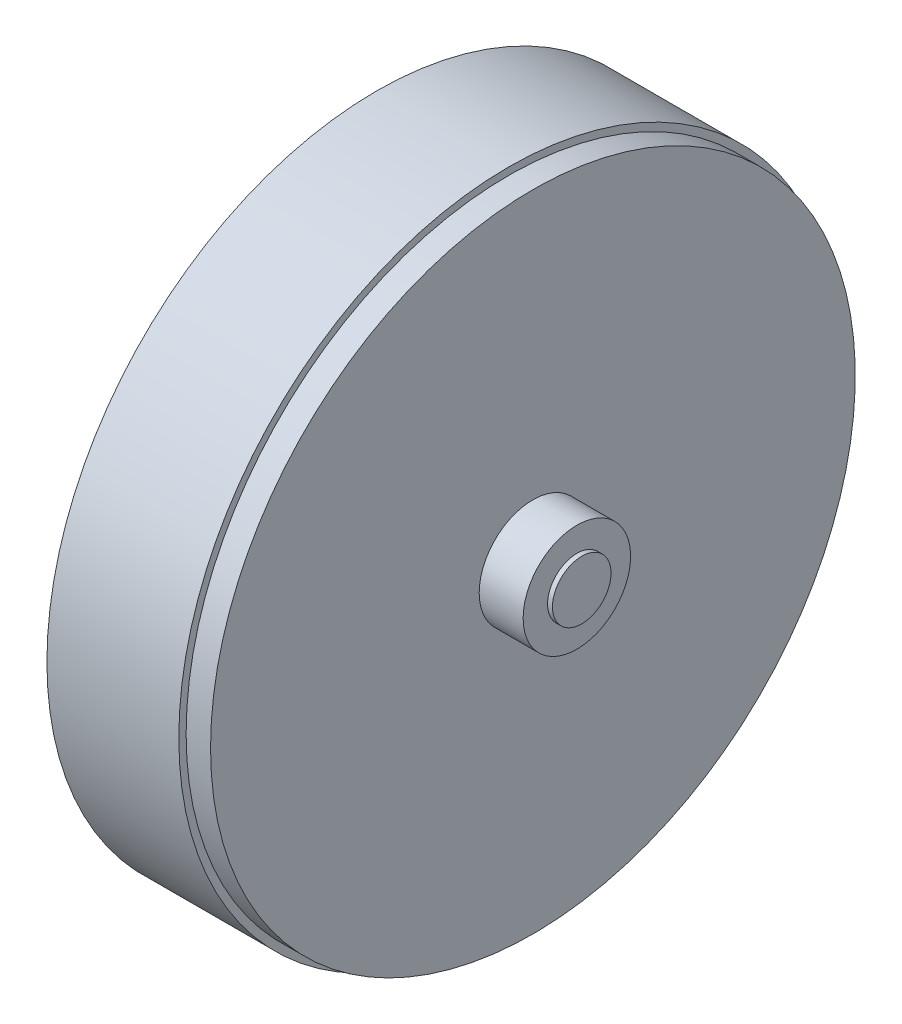
SolidWorks part; units mm, degrees
material "1060 Alloy"
ref_plane "Front Plane" through (0, 0, 0) normal (0, 0, 1) x (1, 0, 0)
ref_plane "Top Plane" through (0, 0, 0) normal (0, 1, 0) x (1, 0, 0)
ref_plane "Right Plane" through (0, 0, 0) normal (1, 0, 0) x (0, 0, -1)
sketch "Sketch1" plane through (0, 0, 0) normal (0, 0, 1) x (1, 0, 0)
  line L0 (-34.0089, 0) -> (27.2771, 0) construction
  line L1 (0, 0) -> (0, 3)
  line L7 (-7.5, 33.75) -> (-21, 33.75)
  line L8 (-21, 33.75) -> (-21, 22)
  line L10 (-21, 22) -> (-25, 22)
  line L11 (-25, 22) -> (-25, 18)
  line L13 (-30.5, 17) -> (-30.5, 0)
  line L14 (0, 3) -> (-0.5, 3)
  line L15 (-0.5, 3) -> (-0.5, 5.5)
  line L16 (-0.5, 5.5) -> (-5, 5.5)
  line L18 (-5, 5.5) -> (-5, 33)
  line L19 (-7.5, 33.75) -> (-7.5, 33)
  line L20 (-7.5, 33) -> (-5, 33)
  line L21 (-25, 18) -> (-27, 18)
  line L22 (-27, 18) -> (-27, 17)
  line L23 (-27, 17) -> (-30.5, 17)
  line L25 (-30.5, 0) -> (0, 0)
  point P2 (-28.75, 17)
  point P20 (0, 0)
  point P21 (0, 0)
  dimension "D1" = 6
  dimension "D2" = 0.5
  dimension "D3" = 11
  dimension "D4" = 5
  dimension "D5" = 7.5
  dimension "D6" = 66
  dimension "D7" = 16
  dimension "D8" = 67.5
  dimension "D9" = 44
  dimension "D10" = 20
  dimension "D11" = 36
  dimension "D12" = 34
  dimension "D13" = 2
  dimension "D14" = 5.5
revolve "Revolve1" add sketch "Sketch1" angle 360 about L0
sketch "Sketch2" plane through (-25, 0, 0) normal (-1, 0, 0) x (0, 0, 1)
  circle A0 centre (0, 0) radius 20.25 construction
  circle A1 centre (-7.7493, 18.7086) radius 1.25
  circle A2 centre (7.7493, 18.7086) radius 1.25
  circle A3 centre (18.7086, 7.7493) radius 1.25
  circle A4 centre (18.7086, -7.7493) radius 1.25
  circle A5 centre (7.7493, -18.7086) radius 1.25
  circle A6 centre (-7.7493, -18.7086) radius 1.25
  circle A7 centre (-18.7086, -7.7493) radius 1.25
  circle A8 centre (-18.7086, 7.7493) radius 1.25
  point P6 (0, 0)
  point P7 (0, 0)
  point P21 (0, 0)
  point P22 (0, 0)
  dimension "D1" = 40.5
  dimension "D2" = 2.5
  dimension "D3" = 8
extrude "Cut-Extrude1" cut sketch "Sketch2" against normal blind 4
